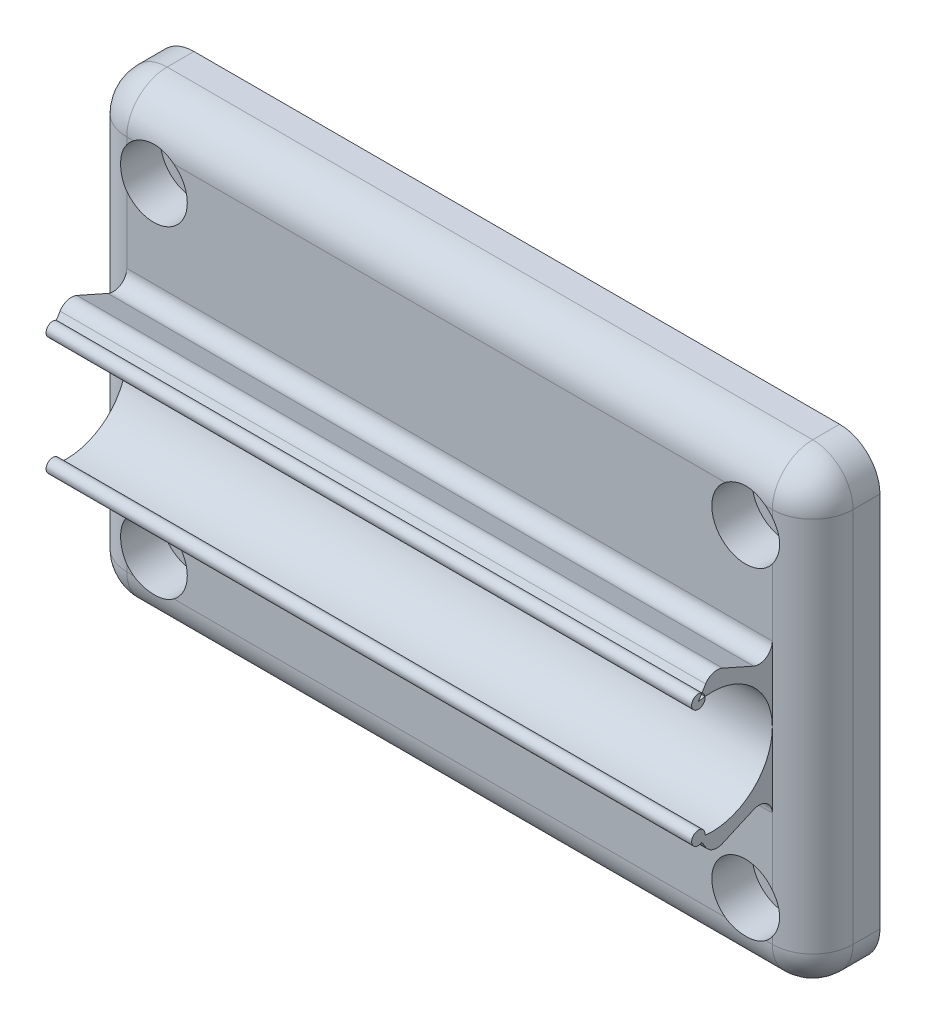
SolidWorks part; units mm, degrees
ref_plane "Front Plane" through (0, 0, 0) normal (0, 0, 1) x (1, 0, 0)
ref_plane "Top Plane" through (0, 0, 0) normal (0, 1, 0) x (1, 0, 0)
ref_plane "Right Plane" through (0, 0, 0) normal (1, 0, 0) x (0, 0, -1)
sketch "Sketch1" plane through (0, 0, 0) normal (0, 0, 1) x (1, 0, 0)
  line L0 (5, 4.776) -> (5, -40.3355) construction
  line L1 (0, 0) -> (54, 0)
  line L2 (0, 0) -> (0, -34)
  line L3 (0, -34) -> (54, -34)
  line L4 (54, 0) -> (54, -34)
  line L5 (49, 4.776) -> (49, -41.3745) construction
  line L6 (-4.4873, -5) -> (65.7343, -5) construction
  line L7 (-5.9593, -29) -> (72.2282, -29) construction
  circle A0 centre (5, -5) radius 1
  circle A1 centre (49, -5) radius 1
  circle A2 centre (49, -29) radius 1
  circle A3 centre (5, -29) radius 1
  dimension "D7" = 2
  dimension "D8" = 2
  dimension "D9" = 2
  dimension "D10" = 2
  dimension "D1" = 54
  dimension "D2" = 34
  dimension "D3" = 5
  dimension "D4" = 5
  dimension "D5" = 5
  dimension "D6" = 5
extrude "Boss-Extrude1" add sketch "Sketch1" along normal blind 5
fillet "Fillet2" radius 3 8 edges at (0, -17, 5) (27, -34, 5) (54, -17, 5) (27, 0, 5) (54, 0, 2.5) (0, 0, 2.5) (0, -34, 2.5) (54, -34, 2.5)
sketch "Sketch2" plane through (0, 0, 5) normal (0, 0, 1) x (1, 0, 0)
  circle A0 centre (5, -5) radius 2.5
  circle A1 centre (5, -29) radius 2.5
  circle A2 centre (49, -29) radius 2.5
  circle A3 centre (49, -5) radius 2.5
  dimension "D1" = 5
  dimension "D2" = 5
  dimension "D3" = 5
  dimension "D4" = 5
extrude "Cut-Extrude1" cut sketch "Sketch2" against normal blind 3
ref_plane "Plane1" through (44, 0, 0) normal (1, 0, 0) x (0, 0, -1)
sketch "Sketch4" plane through (44, 0, 0) normal (1, 0, 0) x (0, 0, -1)
  line L0 (-5, -3) -> (-5, -31) construction
  line L1 (-5, -17) -> (-24.7424, -17) construction
  line L2 (-9.5, -5.6804) -> (-9.5, -33.279) construction
  line L3 (-10.5, -5.6804) -> (-10.5, -29.8067) construction
  line L4 (-6.3908, -13) -> (-3.6958, -13) construction
  line L5 (-5.5486, -21) -> (-3.0895, -21) construction
  line L6 (-10.0626, -11) -> (-8.3109, -11) construction
  line L7 (-10.0626, -23) -> (-8.3109, -23) construction
  line L8 (-10.5, -21.3875) -> (-9.5, -23)
  line L9 (-9.5, -23) -> (-5, -21)
  line L10 (-5, -21) -> (-5, -17)
  line L11 (-10.5, -12.6125) -> (-9.5, -11)
  line L12 (-9.5, -11) -> (-5, -13)
  line L13 (-5, -13) -> (-5, -17)
  arc A0 (-10.5, -21.3875) -> (-10.5, -12.6125) centre (-9.5, -17) ccw
  circle A1 centre (-10.5, -12.6125) radius 0.5
  circle A2 centre (-10.5, -21.3875) radius 0.5
  dimension "D3" = 1
  dimension "D4" = 1
  dimension "D1" = 4.5
  dimension "D2" = 1
  dimension "D5" = 4
  dimension "D6" = 2
  dimension "D7" = 4
  dimension "D8" = 2
  dimension "D9" = 262.157
  dimension "D10" = 262.157
extrude "Boss-Extrude2" add sketch "Sketch4" along normal blind 7 and the other way blind 41 contours A1 A0 L13 L12 L11 | A2 L8 L9 L10 A0 | L11 A1 A0
fillet "Fillet3" radius 1 4 edges at (27, -21, 5) (27, -13, 5) (27, -23, 9.5) (27, -11, 9.5)
